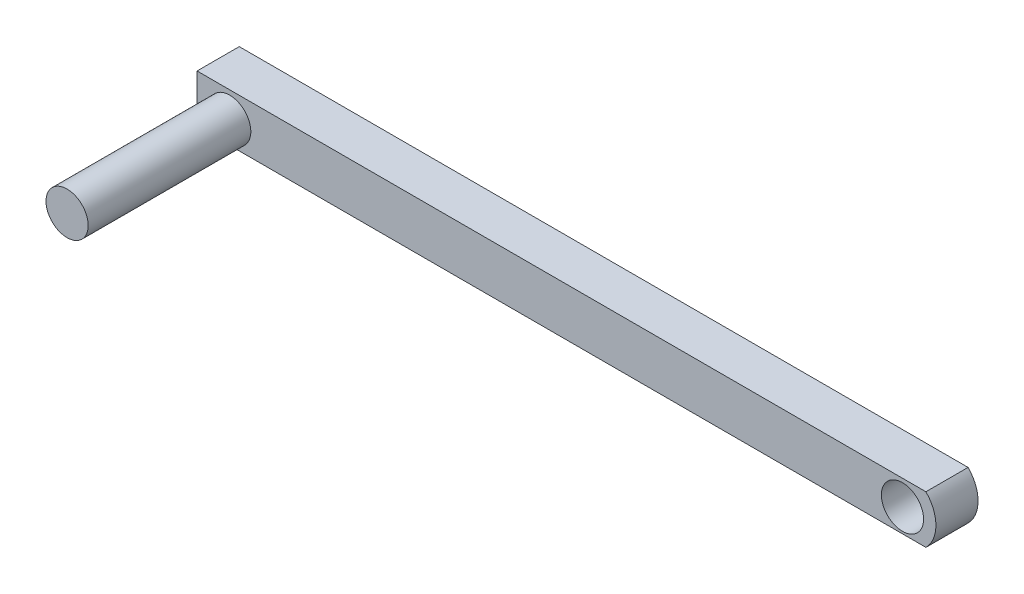
SolidWorks part; units mm, degrees
material "AA356.0-F"
ref_plane "Front Plane" through (0, 0, 0) normal (0, 0, 1) x (1, 0, 0)
ref_plane "Top Plane" through (0, 0, 0) normal (0, 1, 0) x (1, 0, 0)
ref_plane "Right Plane" through (0, 0, 0) normal (1, 0, 0) x (0, 0, -1)
sketch "Sketch1" plane through (0, 0, 0) normal (0, 0, 1) x (1, 0, 0)
  line L1 (-107.3718, 35.7906) -> (142.6282, 35.7906)
  line L2 (-107.3718, 35.7906) -> (-107.3718, 19.7906)
  line L3 (-107.3718, 19.7906) -> (142.6282, 19.7906)
  line L4 (142.6282, 35.7906) -> (142.6282, 19.7906)
  dimension "D1" = 250
  dimension "D2" = 16
extrude "Boss-Extrude1" add sketch "Sketch1" along normal blind 14
sketch "Sketch2" plane through (0, 0, 14) normal (0, 0, 1) x (1, 0, 0)
  circle A0 centre (126.8323, 27.5189) radius 7
extrude "Cut-Extrude1" cut sketch "Sketch2" against normal through all
sketch "Sketch3" plane through (0, 0, 14) normal (0, 0, 1) x (1, 0, 0)
  line L0 (142.6282, 35.7906) -> (-107.3718, 35.7906) construction
  line L1 (-107.3718, 19.7906) -> (142.6282, 19.7906) construction
  line L2 (142.6282, 19.7906) -> (134.6128, 19.7906)
  line L3 (134.6128, 35.7906) -> (142.6282, 35.7906)
  line L4 (142.6282, 35.7906) -> (142.6282, 19.7906)
  arc A0 (134.6128, 35.7906) -> (134.6128, 19.7906) centre (126.6128, 27.7906) cw
extrude "Cut-Extrude3" cut sketch "Sketch3" against normal through all
sketch "Sketch4" plane through (0, 0, 14) normal (0, 0, 1) x (1, 0, 0)
  circle A0 centre (-96.5317, 27.2646) radius 7
extrude "Boss-Extrude2" add sketch "Sketch4" along normal blind 14
sketch "Sketch5" plane through (0, 0, 28) normal (0, 0, 1) x (1, 0, 0)
  circle A0 centre (-96.5317, 27.2646) radius 7
extrude "Boss-Extrude3" add sketch "Sketch5" along normal blind 40
